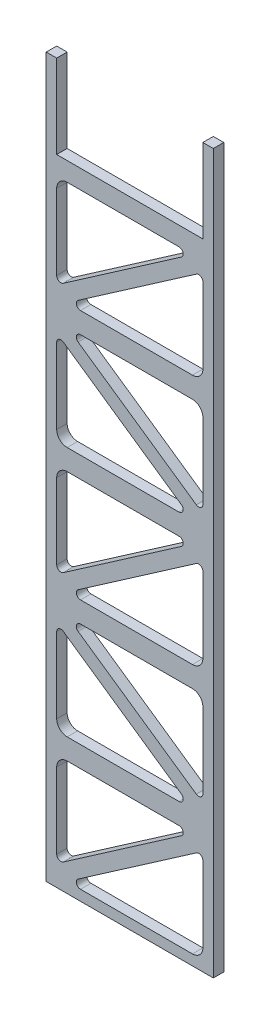
SolidWorks part; units mm, degrees
ref_plane "Front Plane" through (0, 0, 0) normal (0, 0, 1) x (1, 0, 0)
ref_plane "Top Plane" through (0, 0, 0) normal (0, 1, 0) x (1, 0, 0)
ref_plane "Right Plane" through (0, 0, 0) normal (1, 0, 0) x (0, 0, -1)
sketch "Model" plane through (0, 0, 0) normal (0, 0, 1) x (1, 0, 0)
  line L0 (-80.7688, 311.15) -> (-12.7, 311.15)
  line L1 (-10.3358, 365.5406) -> (-82.2146, 315.7784)
  line L2 (-6.35, 317.5) -> (-6.35, 363.4522)
  line L3 (-95.25, 287.2522) -> (-95.25, 241.3)
  line L4 (-19.3854, 239.5784) -> (-91.2642, 289.3406)
  line L5 (-88.9, 234.95) -> (-20.8312, 234.95)
  line L6 (-80.7688, 158.75) -> (-12.7, 158.75)
  line L7 (-10.3358, 213.1406) -> (-82.2146, 163.3784)
  line L8 (-6.35, 165.1) -> (-6.35, 211.0522)
  line L9 (-20.8312, 222.25) -> (-88.9, 222.25)
  line L10 (-91.2642, 167.8594) -> (-19.3854, 217.6216)
  line L11 (-95.25, 215.9) -> (-95.25, 169.9478)
  line L12 (-82.2146, 293.8216) -> (-10.3358, 244.0594)
  line L13 (-12.7, 298.45) -> (-80.7688, 298.45)
  line L14 (-6.35, 246.1478) -> (-6.35, 292.1)
  line L15 (-95.25, 134.8522) -> (-95.25, 88.9)
  line L16 (-19.3854, 87.1784) -> (-91.2642, 136.9406)
  line L17 (-88.9, 82.55) -> (-20.8312, 82.55)
  line L18 (-80.7688, 6.35) -> (-12.7, 6.35)
  line L19 (-10.3358, 60.7406) -> (-82.2146, 10.9784)
  line L20 (-6.35, 12.7) -> (-6.35, 58.6522)
  line L21 (-20.8312, 69.85) -> (-88.9, 69.85)
  line L22 (-91.2642, 15.4594) -> (-19.3854, 65.2216)
  line L23 (-95.25, 63.5) -> (-95.25, 17.5478)
  line L24 (-20.8312, 374.65) -> (-88.9, 374.65)
  line L25 (-91.2642, 320.2594) -> (-19.3854, 370.0216)
  line L26 (-95.25, 368.3) -> (-95.25, 322.3478)
  line L27 (-82.2146, 141.4216) -> (-10.3358, 91.6594)
  line L28 (-12.7, 146.05) -> (-80.7688, 146.05)
  line L29 (-6.35, 93.7478) -> (-6.35, 139.7)
  line L30 (-95.25, 386.08) -> (-6.35, 386.08)
  line L31 (-95.25, 386.08) -> (-95.25, 436.88)
  line L32 (-101.6, 436.88) -> (-95.25, 436.88)
  line L33 (-101.6, 0) -> (-101.6, 436.88)
  line L34 (-101.6, 0) -> (0, 0)
  line L35 (0, 0) -> (0, 436.88)
  line L36 (-6.35, 436.88) -> (0, 436.88)
  line L37 (-6.35, 386.08) -> (-6.35, 436.88)
  arc A0 (-12.7, 311.15) -> (-6.35, 317.5) centre (-12.7, 317.5) ccw
  arc A1 (-82.2146, 315.7784) -> (-80.7688, 311.15) centre (-80.7688, 313.69) ccw
  arc A2 (-6.35, 363.4522) -> (-10.3358, 365.5406) centre (-8.89, 363.4522) ccw
  arc A3 (-95.25, 241.3) -> (-88.9, 234.95) centre (-88.9, 241.3) ccw
  arc A4 (-91.2642, 289.3406) -> (-95.25, 287.2522) centre (-92.71, 287.2522) ccw
  arc A5 (-20.8312, 234.95) -> (-19.3854, 239.5784) centre (-20.8312, 237.49) ccw
  arc A6 (-12.7, 158.75) -> (-6.35, 165.1) centre (-12.7, 165.1) ccw
  arc A7 (-82.2146, 163.3784) -> (-80.7688, 158.75) centre (-80.7688, 161.29) ccw
  arc A8 (-6.35, 211.0522) -> (-10.3358, 213.1406) centre (-8.89, 211.0522) ccw
  arc A9 (-88.9, 222.25) -> (-95.25, 215.9) centre (-88.9, 215.9) ccw
  arc A10 (-19.3854, 217.6216) -> (-20.8312, 222.25) centre (-20.8312, 219.71) ccw
  arc A11 (-95.25, 169.9478) -> (-91.2642, 167.8594) centre (-92.71, 169.9478) ccw
  arc A12 (-10.3358, 244.0594) -> (-6.35, 246.1478) centre (-8.89, 246.1478) ccw
  arc A13 (-80.7688, 298.45) -> (-82.2146, 293.8216) centre (-80.7688, 295.91) ccw
  arc A14 (-6.35, 292.1) -> (-12.7, 298.45) centre (-12.7, 292.1) ccw
  arc A15 (-95.25, 88.9) -> (-88.9, 82.55) centre (-88.9, 88.9) ccw
  arc A16 (-91.2642, 136.9406) -> (-95.25, 134.8522) centre (-92.71, 134.8522) ccw
  arc A17 (-20.8312, 82.55) -> (-19.3854, 87.1784) centre (-20.8312, 85.09) ccw
  arc A18 (-12.7, 6.35) -> (-6.35, 12.7) centre (-12.7, 12.7) ccw
  arc A19 (-82.2146, 10.9784) -> (-80.7688, 6.35) centre (-80.7688, 8.89) ccw
  arc A20 (-6.35, 58.6522) -> (-10.3358, 60.7406) centre (-8.89, 58.6522) ccw
  arc A21 (-88.9, 69.85) -> (-95.25, 63.5) centre (-88.9, 63.5) ccw
  arc A22 (-19.3854, 65.2216) -> (-20.8312, 69.85) centre (-20.8312, 67.31) ccw
  arc A23 (-95.25, 17.5478) -> (-91.2642, 15.4594) centre (-92.71, 17.5478) ccw
  arc A24 (-88.9, 374.65) -> (-95.25, 368.3) centre (-88.9, 368.3) ccw
  arc A25 (-19.3854, 370.0216) -> (-20.8312, 374.65) centre (-20.8312, 372.11) ccw
  arc A26 (-95.25, 322.3478) -> (-91.2642, 320.2594) centre (-92.71, 322.3478) ccw
  arc A27 (-10.3358, 91.6594) -> (-6.35, 93.7478) centre (-8.89, 93.7478) ccw
  arc A28 (-80.7688, 146.05) -> (-82.2146, 141.4216) centre (-80.7688, 143.51) ccw
  arc A29 (-6.35, 139.7) -> (-12.7, 146.05) centre (-12.7, 139.7) ccw
extrude "Boss-Extrude1" add sketch "Model" along normal blind 6.35
equation "\"thick\"=0.25"
equation "\"D1@Boss-Extrude1\"=\"thick\""
